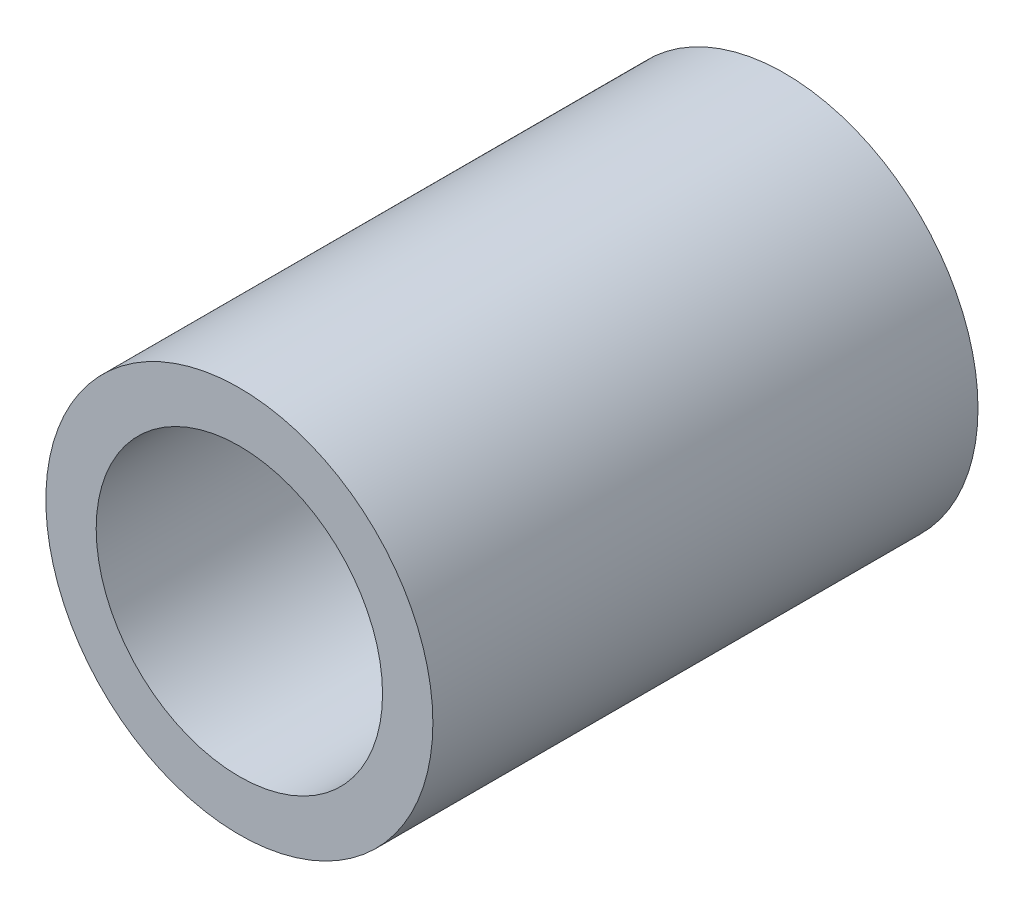
SolidWorks part; units mm, degrees
material "AISI 316  (SS)"
ref_plane "Front Plane" through (0, 0, 0) normal (0, 0, 1) x (1, 0, 0)
ref_plane "Top Plane" through (0, 0, 0) normal (0, 1, 0) x (1, 0, 0)
ref_plane "Right Plane" through (0, 0, 0) normal (1, 0, 0) x (0, 0, -1)
sketch "Sketch1" plane through (0, 0, 0) normal (0, 0, 1) x (1, 0, 0)
  circle A0 centre (0, 0) radius 10.65
  dimension "D1" = 21.3
extrude "Extrude-Thin1" add sketch "Sketch1" along normal blind 30 thin thin type one direction reverse wall 2.77
